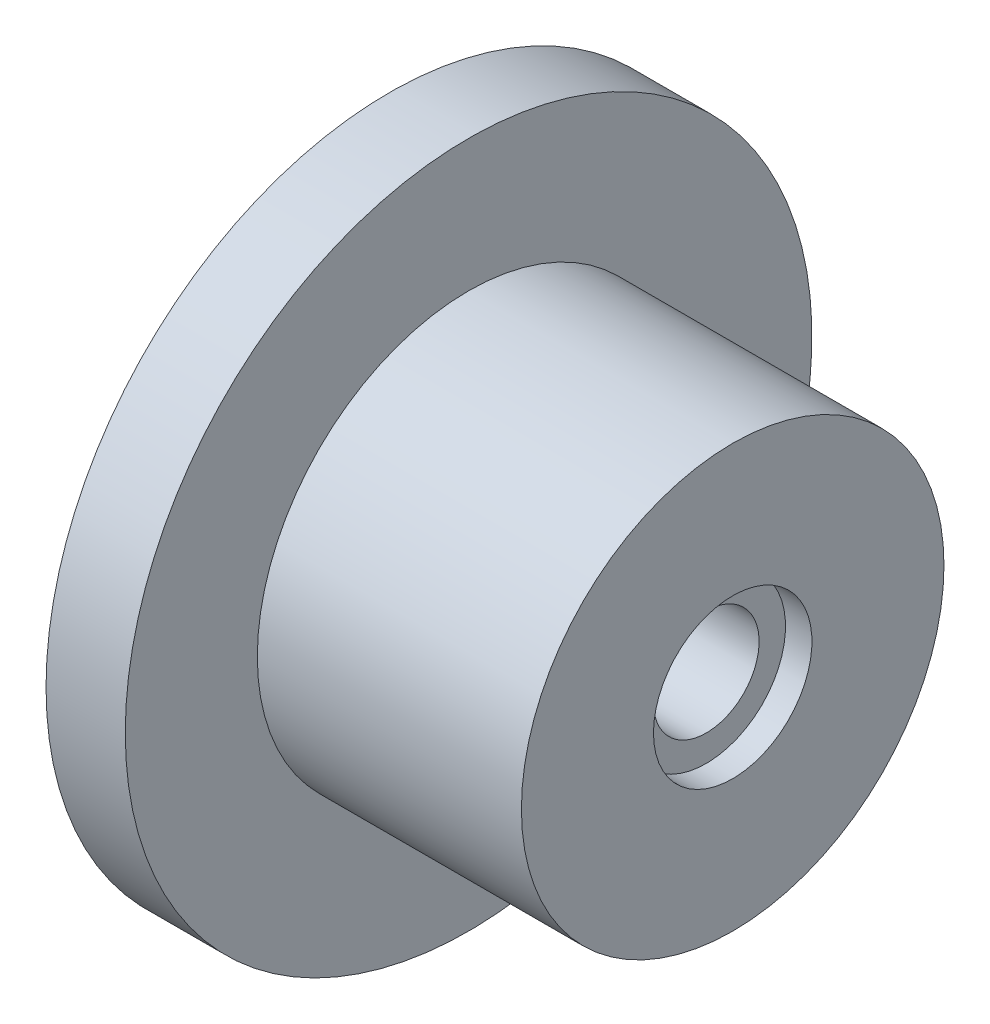
SolidWorks part; units mm, degrees
ref_plane "Front Plane" through (0, 0, 0) normal (0, 0, 1) x (1, 0, 0)
ref_plane "Top Plane" through (0, 0, 0) normal (0, 1, 0) x (1, 0, 0)
ref_plane "Right Plane" through (0, 0, 0) normal (1, 0, 0) x (0, 0, -1)
sketch "Sketch1" plane through (0, 0, 0) normal (0, 0, 1) x (1, 0, 0)
  line L0 (0, 0) -> (9, 0) construction
  line L1 (0, 4) -> (0, 2)
  line L2 (8, 3) -> (9, 3)
  line L3 (9, 3) -> (9, 8)
  line L4 (9, 8) -> (-1, 8)
  line L5 (-1, 8) -> (-1, 13)
  line L6 (-1, 13) -> (-4, 13)
  line L7 (-4, 13) -> (-4, 4)
  line L8 (-4, 4) -> (0, 4)
  line L9 (0, 2) -> (8, 2)
  line L10 (8, 2) -> (8, 3)
  point P8 (0, 0)
  point P14 (0, 0)
  dimension "D1" = 3
  dimension "D2" = 9
  dimension "D3" = 5
  dimension "D4" = 4
  dimension "D5" = 5
  dimension "D7" = 10
  dimension "D8" = 9
  dimension "D9" = 1
  dimension "D10" = 1
  dimension "D11" = 2
revolve "Revolve1" add sketch "Sketch1" angle 360 about L0
